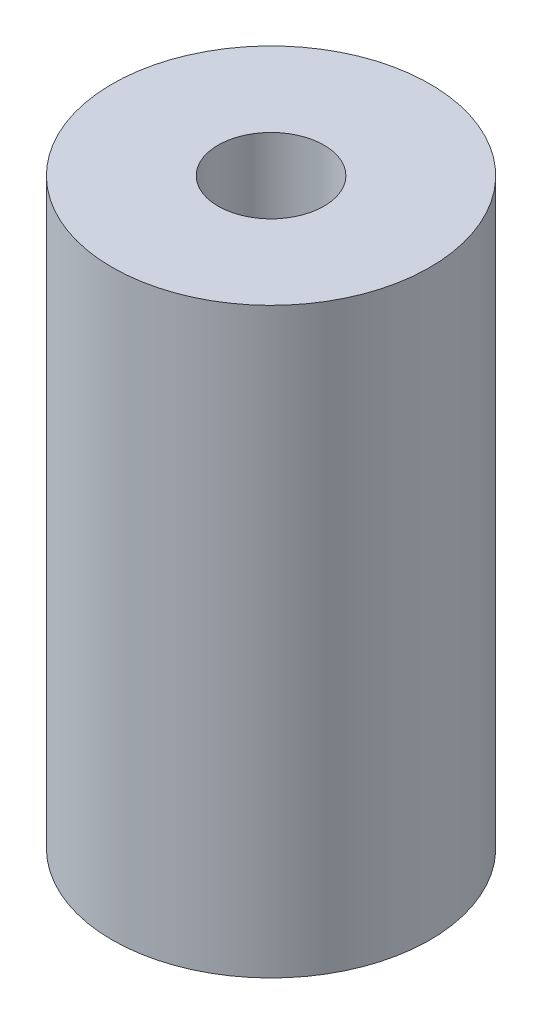
SolidWorks part; units mm, degrees
ref_plane "Front Plane" through (0, 0, 0) normal (0, 0, 1) x (1, 0, 0)
ref_plane "Top Plane" through (0, 0, 0) normal (0, 1, 0) x (1, 0, 0)
ref_plane "Right Plane" through (0, 0, 0) normal (1, 0, 0) x (0, 0, -1)
sketch "Sketch1" plane through (0, 0, 0) normal (0, 1, 0) x (1, 0, 0)
  circle A0 centre (0, 0) radius 1.5875
  circle A1 centre (0, 0) radius 4.7625
  dimension "D1" = 3.175
  dimension "D2" = 9.525
extrude "Boss-Extrude1" add sketch "Sketch1" along normal blind 17.4625
